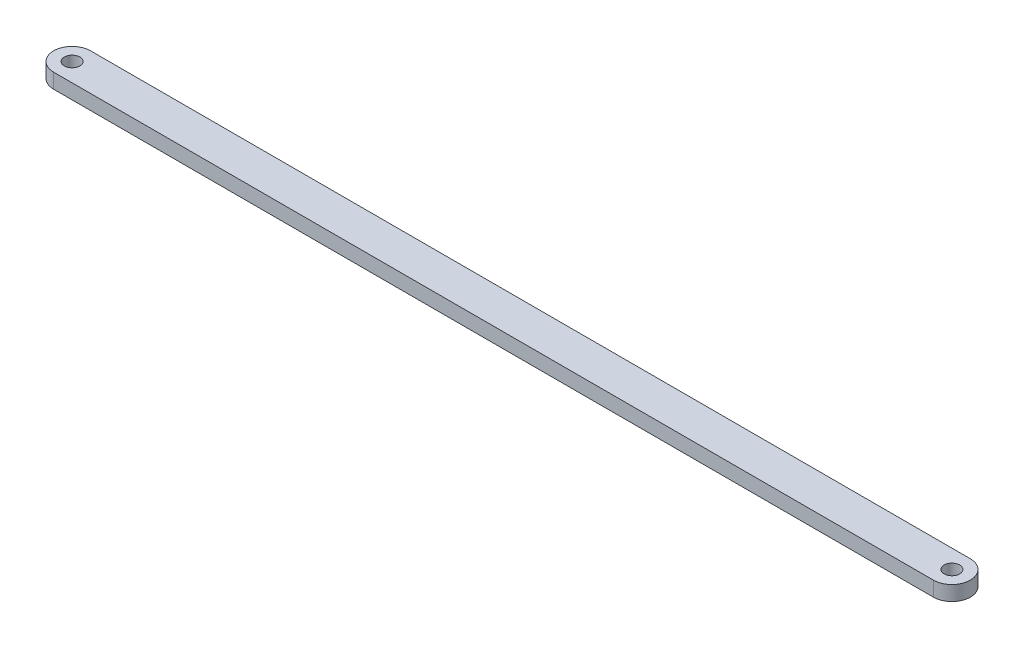
SolidWorks part; units mm, degrees
ref_plane "Front Plane" through (0, 0, 0) normal (0, 0, 1) x (1, 0, 0)
ref_plane "Top Plane" through (0, 0, 0) normal (0, 1, 0) x (1, 0, 0)
ref_plane "Right Plane" through (0, 0, 0) normal (1, 0, 0) x (0, 0, -1)
sketch "Sketch1" plane through (0, 0, 0) normal (0, 1, 0) x (1, 0, 0)
  line L0 (0, 0) -> (119, 0) construction
  line L1 (0, 2.5) -> (119, 2.5)
  line L2 (0, -2.5) -> (119, -2.5)
  arc A0 (0, 2.5) -> (0, -2.5) centre (0, 0) ccw
  arc A1 (119, -2.5) -> (119, 2.5) centre (119, 0) ccw
  circle A2 centre (0, 0) radius 1.05
  circle A3 centre (119, 0) radius 1.05
  point P3 (59.5, 0)
  dimension "D1" = 2.5
  dimension "D3" = 2.1
  dimension "D4" = 2.1
  dimension "D2" = 119
extrude "Boss-Extrude1" add sketch "Sketch1" along normal blind 2
